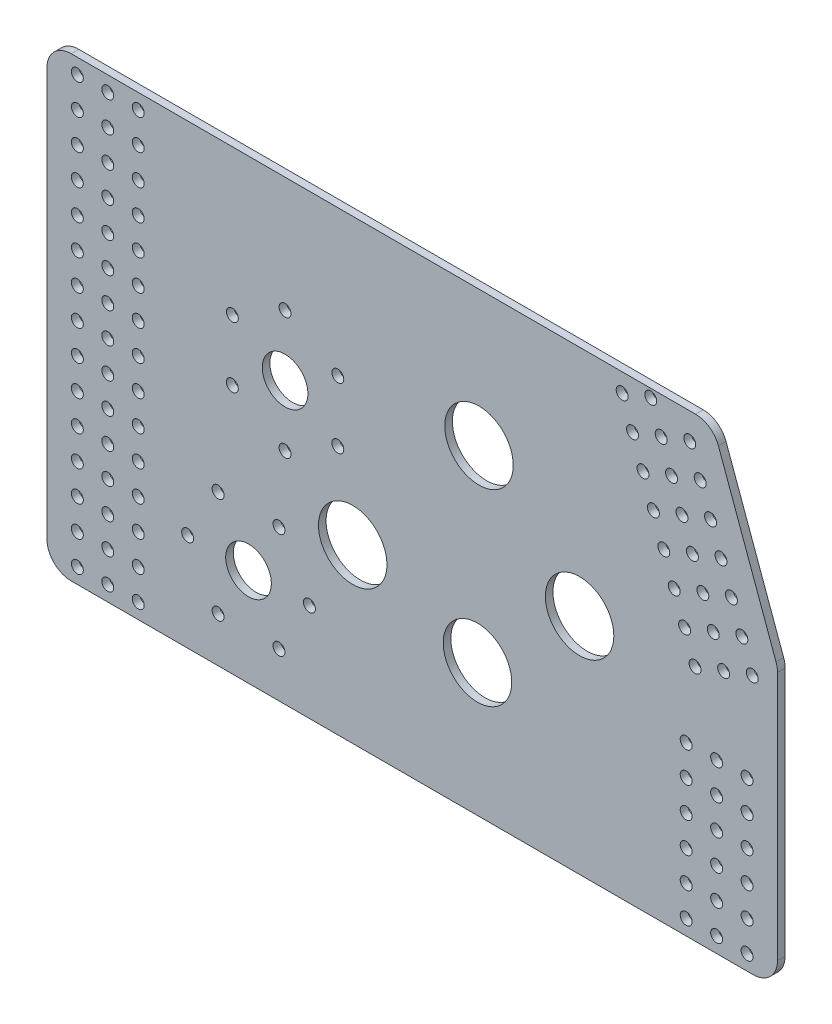
SolidWorks part; units mm, degrees
ref_plane "Front Plane" through (0, 0, 0) normal (0, 0, 1) x (1, 0, 0)
ref_plane "Top Plane" through (0, 0, 0) normal (0, 1, 0) x (1, 0, 0)
ref_plane "Right Plane" through (0, 0, 0) normal (1, 0, 0) x (0, 0, -1)
sketch "Sketch1" plane through (0, 0, 0) normal (0, 0, 1) x (1, 0, 0)
  line B0 (-152.4, 0) -> (152.4, 0)
  line B1 (152.4, 0) -> (152.4, 116.0843)
  line B2 (152.4, 116.0843) -> (125.3149, 190.5)
  line B3 (125.3149, 190.5) -> (-152.4, 190.5)
  line B4 (-152.4, 190.5) -> (-152.4, 0)
  circle B5 centre (-139.7, 184.15) radius 2.4892
  circle B6 centre (-127, 184.15) radius 2.4892
  circle B7 centre (-114.3, 184.15) radius 2.4892
  circle B8 centre (-127, 171.45) radius 2.4892
  circle B9 centre (-114.3, 171.45) radius 2.4892
  circle B10 centre (-127, 158.75) radius 2.4892
  circle B11 centre (-114.3, 158.75) radius 2.4892
  circle B12 centre (-127, 146.05) radius 2.4892
  circle B13 centre (-114.3, 146.05) radius 2.4892
  circle B14 centre (-127, 133.35) radius 2.4892
  circle B15 centre (-114.3, 133.35) radius 2.4892
  circle B16 centre (-127, 120.65) radius 2.4892
  circle B17 centre (-114.3, 120.65) radius 2.4892
  circle B18 centre (-127, 107.95) radius 2.4892
  circle B19 centre (-114.3, 107.95) radius 2.4892
  circle B20 centre (-127, 95.25) radius 2.4892
  circle B21 centre (-114.3, 95.25) radius 2.4892
  circle B22 centre (-127, 82.55) radius 2.4892
  circle B23 centre (-114.3, 82.55) radius 2.4892
  circle B24 centre (-127, 69.85) radius 2.4892
  circle B25 centre (-114.3, 69.85) radius 2.4892
  circle B26 centre (-127, 57.15) radius 2.4892
  circle B27 centre (-114.3, 57.15) radius 2.4892
  circle B28 centre (-127, 44.45) radius 2.4892
  circle B29 centre (-114.3, 44.45) radius 2.4892
  circle B30 centre (-127, 31.75) radius 2.4892
  circle B31 centre (-114.3, 31.75) radius 2.4892
  circle B32 centre (-127, 19.05) radius 2.4892
  circle B33 centre (-114.3, 19.05) radius 2.4892
  circle B34 centre (-127, 6.35) radius 2.4892
  circle B35 centre (-114.3, 6.35) radius 2.4892
  circle B36 centre (-139.7, 171.45) radius 2.4892
  circle B37 centre (-139.7, 158.75) radius 2.4892
  circle B38 centre (-139.7, 146.05) radius 2.4892
  circle B39 centre (-139.7, 133.35) radius 2.4892
  circle B40 centre (-139.7, 120.65) radius 2.4892
  circle B41 centre (-139.7, 107.95) radius 2.4892
  circle B42 centre (-139.7, 95.25) radius 2.4892
  circle B43 centre (-139.7, 82.55) radius 2.4892
  circle B44 centre (-139.7, 69.85) radius 2.4892
  circle B45 centre (-139.7, 57.15) radius 2.4892
  circle B46 centre (-139.7, 44.45) radius 2.4892
  circle B47 centre (-139.7, 31.75) radius 2.4892
  circle B48 centre (-139.7, 19.05) radius 2.4892
  circle B49 centre (-139.7, 6.35) radius 2.4892
  circle B50 centre (87.5907, 182.7494) radius 2.4892
  circle B51 centre (99.5248, 187.093) radius 2.4892
  circle B52 centre (115.8026, 179.5026) radius 2.4892
  circle B53 centre (91.9344, 170.8153) radius 2.4892
  circle B54 centre (103.8685, 175.1589) radius 2.4892
  circle B55 centre (120.1462, 167.5685) radius 2.4892
  circle B56 centre (96.278, 158.8812) radius 2.4892
  circle B57 centre (108.2121, 163.2248) radius 2.4892
  circle B58 centre (124.4899, 155.6344) radius 2.4892
  circle B59 centre (100.6217, 146.9471) radius 2.4892
  circle B60 centre (112.5558, 151.2907) radius 2.4892
  circle B61 centre (128.8335, 143.7003) radius 2.4892
  circle B62 centre (104.9653, 135.013) radius 2.4892
  circle B63 centre (116.8994, 139.3566) radius 2.4892
  circle B64 centre (133.1772, 131.7662) radius 2.4892
  circle B65 centre (109.309, 123.0789) radius 2.4892
  circle B66 centre (121.2431, 127.4226) radius 2.4892
  circle B67 centre (137.5208, 119.8321) radius 2.4892
  circle B68 centre (113.6526, 111.1448) radius 2.4892
  circle B69 centre (125.5867, 115.4885) radius 2.4892
  circle B70 centre (141.8645, 107.898) radius 2.4892
  circle B71 centre (117.9963, 99.2107) radius 2.4892
  circle B72 centre (129.9304, 103.5544) radius 2.4892
  circle B73 centre (146.2081, 95.9639) radius 2.4892
  circle B74 centre (114.3, 69.85) radius 2.4892
  circle B75 centre (127, 69.85) radius 2.4892
  circle B76 centre (139.7, 69.85) radius 2.4892
  circle B77 centre (114.3, 57.15) radius 2.4892
  circle B78 centre (127, 57.15) radius 2.4892
  circle B79 centre (139.7, 57.15) radius 2.4892
  circle B80 centre (114.3, 44.45) radius 2.4892
  circle B81 centre (127, 44.45) radius 2.4892
  circle B82 centre (139.7, 44.45) radius 2.4892
  circle B83 centre (114.3, 31.75) radius 2.4892
  circle B84 centre (127, 31.75) radius 2.4892
  circle B85 centre (139.7, 31.75) radius 2.4892
  circle B86 centre (114.3, 19.05) radius 2.4892
  circle B87 centre (127, 19.05) radius 2.4892
  circle B88 centre (139.7, 19.05) radius 2.4892
  circle B89 centre (114.3, 6.35) radius 2.4892
  circle B90 centre (127, 6.35) radius 2.4892
  circle B91 centre (139.7, 6.35) radius 2.4892
  circle B92 centre (11.8508, 132.0168) radius 14.2875
  circle B93 centre (-24.8197, 71.7449) radius 14.2875
  circle B94 centre (57.6351, 95.7125) radius 14.2875
  circle B95 centre (23.7546, 49.6787) radius 14.2875
  circle B96 centre (-65.2702, 36.9534) radius 9.525
  circle B97 centre (-65.2702, 106.5494) radius 9.525
  circle B98 centre (-65.2702, 131.9494) radius 2.4892
  circle B99 centre (-65.2702, 11.5534) radius 2.4892
  circle B100 centre (-43.2731, 119.2494) radius 2.4892
  circle B101 centre (-43.2731, 93.8494) radius 2.4892
  circle B102 centre (-65.2702, 81.1494) radius 2.4892
  circle B103 centre (-87.2672, 93.8494) radius 2.4892
  circle B104 centre (-87.2672, 119.2494) radius 2.4892
  circle B105 centre (-87.2672, 24.2534) radius 2.4892
  circle B106 centre (-87.2672, 49.6534) radius 2.4892
  circle B107 centre (-65.2702, 62.3534) radius 2.4892
  circle B108 centre (-43.2731, 49.6534) radius 2.4892
  circle B109 centre (-43.2731, 24.2534) radius 2.4892
sketch_block_instance "Block-InnerPlate-1"
sketch_block "Block-InnerPlate" parameters "D1"=4.9784, "D7"=4.9784, "D8"=4.9784, "D9"=4.9784, "D11"=4.9784, "D12"=4.9784, "D13"=4.9784, "D15"=19.05, "D16"=19.05, "D17"=28.575, "D18"=28.575, "D19"=28.575, "D20"=28.575, "D21"=4.9784, "D22"=4.9784, "D2"=6.35, "D3"=12.7, "D4"=12.7, "D5"=12.7, "D6"=6.35, "D10"=12.7, "D14"=12.7, "D23"=25.4, "D24"=25.4
extrude "Boss-Extrude1" add sketch "Sketch1" along normal blind 3.175
sketch "Sketch2" plane through (0, 0, 3.175) normal (0, 0, 1) x (1, 0, 0)
  circle A0 centre (146.2081, 95.9639) radius 2.4892
  dimension "D1" = 4.9784
extrude "Boss-Extrude2" add sketch "Sketch2" against normal blind 3.175
fillet "Fillet1" radius 10.16 5 edges at (-152.4, 0, 1.5875) (152.4, 0, 1.5875) (152.4, 116.0843, 1.5875) (125.3149, 190.5, 1.5875) (-152.4, 190.5, 1.5875)
sketch "Sketch3" plane through (0, 0, 3.175) normal (0, 0, 1) x (1, 0, 0)
  line L0 (-65.2702, 106.5494) -> (-39.8702, 106.5494) construction
  line L1 (-65.2702, 36.9534) -> (-39.8702, 36.9534) construction
  circle A0 centre (-65.2702, 106.5494) radius 9.525
  circle A1 centre (-39.8702, 106.5494) radius 2.4892
  circle A2 centre (-52.5702, 84.5524) radius 2.4892
  circle A3 centre (-77.9702, 84.5524) radius 2.4892
  circle A4 centre (-90.6702, 106.5494) radius 2.4892
  circle A5 centre (-77.9702, 128.5465) radius 2.4892
  circle A6 centre (-52.5702, 128.5465) radius 2.4892
  circle A7 centre (-65.2702, 36.9534) radius 9.525
  circle A8 centre (-39.8702, 36.9534) radius 2.4892
  circle A9 centre (-52.5702, 14.9564) radius 2.4892
  circle A10 centre (-77.9702, 14.9564) radius 2.4892
  circle A11 centre (-90.6702, 36.9534) radius 2.4892
  circle A12 centre (-77.9702, 58.9505) radius 2.4892
  circle A13 centre (-52.5702, 58.9505) radius 2.4892
  dimension "D1" = 19.05
  dimension "D2" = 4.9784
  dimension "D7" = 19.05
  dimension "D8" = 4.9784
  dimension "D3" = 25.4
  dimension "D5" = 25.4
  dimension "D6" = 25.4
  dimension "D9" = 25.4
  dimension "D11" = 25.4
  dimension "D4" = 6
  dimension "D10" = 6
extrude "Cut-Extrude1" cut sketch "Sketch3" against normal blind 3.175
sketch "Sketch4" plane through (0, 0, 3.175) normal (0, 0, 1) x (1, 0, 0)
  circle A0 centre (-65.2702, 131.9494) radius 2.4892
  circle A1 centre (-43.2731, 119.2494) radius 2.4892
  circle A2 centre (-43.2731, 93.8494) radius 2.4892
  circle A3 centre (-65.2702, 81.1494) radius 2.4892
  circle A4 centre (-87.2672, 93.8494) radius 2.4892
  circle A5 centre (-87.2672, 119.2494) radius 2.4892
  circle A6 centre (-65.2702, 62.3534) radius 2.4892
  circle A7 centre (-43.2731, 49.6534) radius 2.4892
  circle A8 centre (-43.2731, 24.2534) radius 2.4892
  circle A9 centre (-65.2702, 11.5534) radius 2.4892
  circle A10 centre (-87.2672, 24.2534) radius 2.4892
  circle A11 centre (-87.2672, 49.6534) radius 2.4892
  dimension "D1" = 4.9784
  dimension "D2" = 4.9784
  dimension "D3" = 4.9784
  dimension "D4" = 4.9784
  dimension "D5" = 4.9784
  dimension "D6" = 4.9784
  dimension "D7" = 4.9784
  dimension "D8" = 4.9784
  dimension "D9" = 4.9784
  dimension "D10" = 4.9784
  dimension "D11" = 4.9784
  dimension "D12" = 4.9784
extrude "Boss-Extrude3" add sketch "Sketch4" against normal blind 3.175
sketch "Sketch6" plane through (0, 0, 3.175) normal (0, 0, 1) x (1, 0, 0)
  circle A0 centre (23.7546, 49.6787) radius 14.2875 construction
  circle A1 centre (57.6351, 95.7125) radius 14.2875 construction
  circle A2 centre (11.8508, 132.0168) radius 14.2875 construction
  circle A3 centre (23.7546, 49.6787) radius 14.2875
  circle A4 centre (57.6351, 95.7125) radius 14.2875
  circle A5 centre (11.8508, 132.0168) radius 14.2875
  circle A6 centre (-39.8702, 36.9534) radius 2.4892 construction
  circle A7 centre (-52.5702, 14.9564) radius 2.4892 construction
  circle A8 centre (-77.9702, 14.9564) radius 2.4892 construction
  circle A9 centre (-65.2702, 36.9534) radius 9.525 construction
  circle A10 centre (-90.6702, 36.9534) radius 2.4892 construction
  circle A11 centre (-52.5702, 58.9505) radius 2.4892 construction
  circle A12 centre (-77.9702, 58.9505) radius 2.4892 construction
  circle A13 centre (-52.5702, 84.5524) radius 2.4892 construction
  circle A14 centre (-77.9702, 84.5524) radius 2.4892 construction
  circle A15 centre (-90.6702, 106.5494) radius 2.4892 construction
  circle A16 centre (-65.2702, 106.5494) radius 9.525 construction
  circle A17 centre (-39.8702, 106.5494) radius 2.4892 construction
  circle A18 centre (-52.5702, 128.5465) radius 2.4892 construction
  circle A19 centre (-77.9702, 128.5465) radius 2.4892 construction
  circle A20 centre (-39.8702, 36.9534) radius 2.4892
  circle A21 centre (-52.5702, 14.9564) radius 2.4892
  circle A22 centre (-77.9702, 14.9564) radius 2.4892
  circle A23 centre (-65.2702, 36.9534) radius 9.525
  circle A24 centre (-90.6702, 36.9534) radius 2.4892
  circle A25 centre (-52.5702, 58.9505) radius 2.4892
  circle A26 centre (-77.9702, 58.9505) radius 2.4892
  circle A27 centre (-52.5702, 84.5524) radius 2.4892
  circle A28 centre (-77.9702, 84.5524) radius 2.4892
  circle A29 centre (-90.6702, 106.5494) radius 2.4892
  circle A30 centre (-65.2702, 106.5494) radius 9.525
  circle A31 centre (-39.8702, 106.5494) radius 2.4892
  circle A32 centre (-52.5702, 128.5465) radius 2.4892
  circle A33 centre (-77.9702, 128.5465) radius 2.4892
extrude "Boss-Extrude4" add sketch "Sketch6" against normal up to surface (3.175 mm away) up to face at (-37.381, 36.9534, 0)
sketch "Sketch5" plane through (0, 0, 3.175) normal (0, 0, 1) x (1, 0, 0)
  circle A1 centre (-24.8197, 71.7449) radius 14.2875
  circle A2 centre (-24.8197, 71.7449) radius 13.97
  circle A3 centre (27.2348, 55.2349) radius 40.64
  circle A4 centre (27.2348, 55.2349) radius 14.2875
  circle A5 centre (27.2348, 55.2349) radius 22.86
  circle A6 centre (69.8319, 93.3349) radius 34.29
  circle A7 centre (69.8319, 93.3349) radius 14.2875
  circle A8 centre (69.8319, 93.3349) radius 12.7
  circle A9 centre (27.8642, 133.9749) radius 45.72
  circle A10 centre (27.8642, 133.9749) radius 14.2875
  circle A11 centre (-24.8197, 71.7449) radius 14.2875 construction
  dimension "D1" = 27.94
  dimension "D2" = 81.28
  dimension "D3" = 28.575
  dimension "D4" = 45.72
  dimension "D5" = 68.58
  dimension "D6" = 28.575
  dimension "D7" = 25.4
  dimension "D8" = 91.44
  dimension "D12" = 28.575
  dimension "D9" = 16.51
  dimension "D10" = 38.1
  dimension "D11" = 40.64
extrude "Cut-Extrude2" cut sketch "Sketch5" against normal through all contours A4 | A9 A7 A8 | A8 | A7 A9 | A10
sketch "Sketch7" plane through (0, 0, 0) normal (0, 0, 1) x (1, 0, 0)
  circle A0 centre (-55.5743, 18.8147) radius 2.4892
  circle A1 centre (-24.8197, 71.7449) radius 14.2875
  circle A2 centre (-24.8197, 71.7449) radius 45.72 construction
  circle A3 centre (-53.0343, 117.0118) radius 7.62 construction
  circle A4 centre (-24.8197, 71.7449) radius 14.2875 construction
  circle A5 centre (-68.2743, 40.8118) radius 7.62 construction
  circle A6 centre (-53.0343, 117.0118) radius 32.5374 construction
  circle A7 centre (-80.9743, 18.8147) radius 2.4892
  circle A8 centre (-68.2743, 40.8118) radius 32.5374 construction
  circle A9 centre (-93.6743, 40.8118) radius 2.4892
  circle A10 centre (-68.2743, 40.8118) radius 9.525
  circle A11 centre (-42.8743, 40.8118) radius 2.4892
  circle A12 centre (-55.5743, 62.8088) radius 2.4892
  circle A13 centre (-80.9743, 62.8088) radius 2.4892
  circle A14 centre (-31.0373, 104.3118) radius 2.4892
  circle A15 centre (-53.0343, 91.6118) radius 2.4892
  circle A16 centre (-75.0314, 104.3118) radius 2.4892
  circle A17 centre (-53.0343, 117.0118) radius 9.525
  circle A18 centre (-31.0373, 129.7118) radius 2.4892
  circle A19 centre (-53.0343, 142.4118) radius 2.4892
  circle A20 centre (-75.0314, 129.7118) radius 2.4892
  dimension "D1" = 91.44
  dimension "D2" = 15.24
  dimension "D5" = 65.0748
  dimension "D6" = 65.0748
  dimension "D7" = 19.05
  dimension "D8" = 4.9784
  dimension "D9" = 25.4
  dimension "D10" = 25.4
  dimension "D11" = 25.4
  dimension "D14" = 25.4
  dimension "D15" = 25.4
  dimension "D16" = 25.4
  dimension "D17" = 25.4
  dimension "D18" = 25.4
  dimension "D19" = 19.05
  dimension "D20" = 4.9784
  dimension "D3" = 76.2
  dimension "D4" = 15.24
  dimension "D12" = 25.4
  dimension "D13" = 25.4
  dimension "D21" = 25.4
  dimension "D22" = 25.4
  dimension "D23" = 25.4
  dimension "D24" = 25.4
  dimension "D25" = 25.4
  dimension "D26" = 25.4
  dimension "D27" = 25.4
  dimension "D28" = 25.4
  dimension "D29" = 25.4
  dimension "D30" = 25.4
  dimension "D31" = 25.4
extrude "Cut-Extrude3" cut sketch "Sketch7" along normal through all contours A9 | A13 | A11 | A12 | A7 | A0 | A10 | A20 | A17 | A19 | A15 | A14 | A18 | A16
